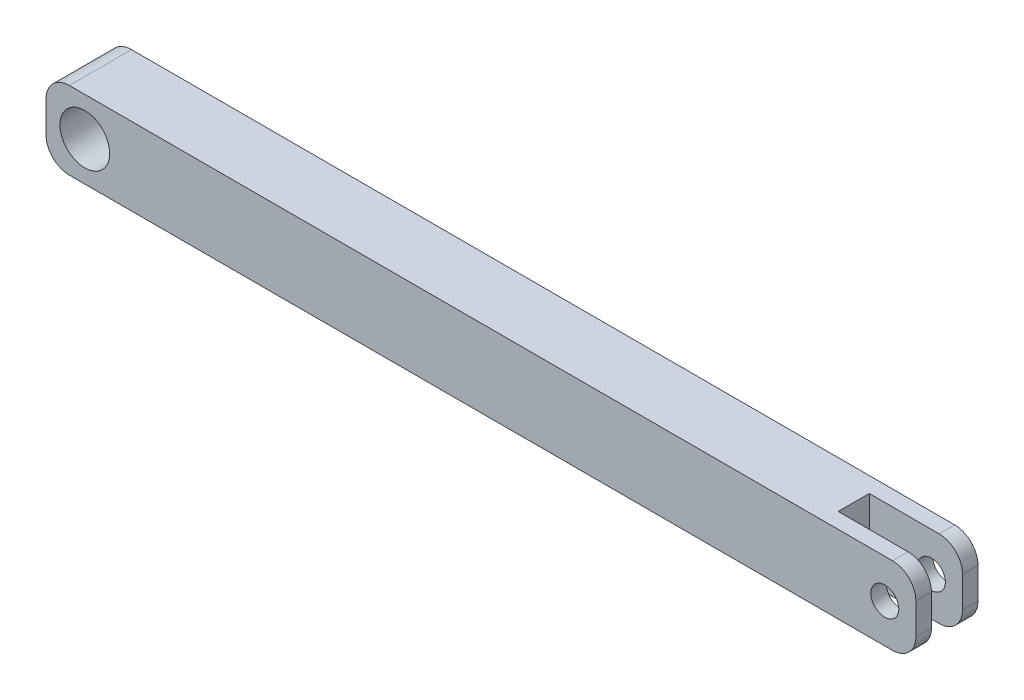
SolidWorks part; units mm, degrees
ref_plane "前视基准面" through (0, 0, 0) normal (0, 0, 1) x (1, 0, 0)
ref_plane "上视基准面" through (0, 0, 0) normal (0, 1, 0) x (1, 0, 0)
ref_plane "右视基准面" through (0, 0, 0) normal (1, 0, 0) x (0, 0, -1)
other "Configuration Table"
sketch "草图5" plane through (0, 0, 0) normal (0, 1, 0) x (1, 0, 0)
  line L0 (0, 0) -> (0, -3)
  line L4 (56, -3) -> (56, 0)
  line L8 (56, 0) -> (0, 0)
  line L9 (0, -3) -> (56, -3)
  dimension "D6" = 3
  dimension "D1" = 56
  dimension "D5" = 3
extrude "凸台-拉伸1" add sketch "草图5" along normal blind 5
sketch "草图6" plane through (0, 0, 3) normal (0, 0, 1) x (1, 0, 0)
  line L2 (0, 5) -> (0, 0) construction
  line L3 (0, 5) -> (56, 5) construction
  circle A0 centre (2.5, 2.5) radius 1.6
  dimension "D1" = 3.2
  dimension "D2" = 2.5
  dimension "D3" = 2.5
extrude "切除-拉伸1" cut sketch "草图6" against normal up to next
sketch "草图7" plane through (0, 0, 0) normal (0, 0, 1) x (1, 0, 0)
  line L0 (56, 5) -> (56, 0) construction
  circle A0 centre (54, 2.5) radius 0.9
  point P6 (56, 2.5)
  dimension "D1" = 1.8
  dimension "D2" = 2
extrude "切除-拉伸2" cut sketch "草图7" along normal up to next
fillet "圆角1" radius 1.5 4 edges at (56, 5, 1.5) (56, 0, 1.5) (0, 0, 1.5) (0, 5, 1.5)
sketch "草图8" plane through (0, 5, 0) normal (0, 1, 0) x (1, 0, 0)
  line L0 (56, 0) -> (56, -3) construction
  line L1 (56, -0.7) -> (50, -0.7)
  line L2 (56, -0.7) -> (56, -2.3)
  line L3 (56, -2.3) -> (50, -2.3)
  line L4 (50, -0.7) -> (50, -2.3)
  point P6 (56, -1.5)
  dimension "D1" = 1.6
  dimension "D2" = 6
extrude "切除-拉伸3" cut sketch "草图8" against normal blind 10
sketch "草图10" plane through (0, 0, 3) normal (0, 0, 1) x (1, 0, 0)
  line L4 (56, 1.5) -> (56, 3.5)
  line L5 (54.5, 5) -> (1.5, 5)
  line L6 (0, 3.5) -> (0, 1.5)
  line L7 (1.5, 0) -> (54.5, 0)
  line L8 (56, 1.5) -> (56, 3.5)
  line L9 (54.5, 5) -> (1.5, 5)
  line L10 (0, 3.5) -> (0, 1.5)
  line L11 (1.5, 0) -> (54.5, 0)
  circle A0 centre (2.5, 2.5) radius 1.6 construction
  circle A1 centre (2.5, 2.5) radius 1.6
  circle A2 centre (54, 2.5) radius 0.9 construction
  circle A3 centre (54, 2.5) radius 0.9
  arc A4 (56, 3.5) -> (54.5, 5) centre (54.5, 3.5) ccw
  arc A5 (1.5, 5) -> (0, 3.5) centre (1.5, 3.5) ccw
  arc A6 (0, 1.5) -> (1.5, 0) centre (1.5, 1.5) ccw
  arc A7 (54.5, 0) -> (56, 1.5) centre (54.5, 1.5) ccw
  arc A8 (56, 3.5) -> (54.5, 5) centre (54.5, 3.5) ccw
  arc A9 (1.5, 5) -> (0, 3.5) centre (1.5, 3.5) ccw
  arc A10 (0, 1.5) -> (1.5, 0) centre (1.5, 1.5) ccw
  arc A11 (54.5, 0) -> (56, 1.5) centre (54.5, 1.5) ccw
  dimension "D1" = 0
extrude "凸台-拉伸2" add sketch "草图10" along normal blind 0.5
sketch "草图11" plane through (0, 0, 0) normal (0, 0, -1) x (-1, 0, 0)
  line L4 (-1.5, 5) -> (-54.5, 5)
  line L5 (-56, 3.5) -> (-56, 1.5)
  line L6 (-54.5, 0) -> (-1.5, 0)
  line L7 (0, 1.5) -> (0, 3.5)
  line L8 (-1.5, 5) -> (-54.5, 5)
  line L9 (-56, 3.5) -> (-56, 1.5)
  line L10 (-54.5, 0) -> (-1.5, 0)
  line L11 (0, 1.5) -> (0, 3.5)
  circle A0 centre (-54, 2.5) radius 0.9 construction
  circle A1 centre (-2.5, 2.5) radius 1.6 construction
  circle A2 centre (-54, 2.5) radius 0.9
  circle A3 centre (-2.5, 2.5) radius 1.6
  arc A4 (-54.5, 5) -> (-56, 3.5) centre (-54.5, 3.5) ccw
  arc A5 (-56, 1.5) -> (-54.5, 0) centre (-54.5, 1.5) ccw
  arc A6 (-1.5, 0) -> (0, 1.5) centre (-1.5, 1.5) ccw
  arc A7 (0, 3.5) -> (-1.5, 5) centre (-1.5, 3.5) ccw
  arc A8 (-54.5, 5) -> (-56, 3.5) centre (-54.5, 3.5) ccw
  arc A9 (-56, 1.5) -> (-54.5, 0) centre (-54.5, 1.5) ccw
  arc A10 (-1.5, 0) -> (0, 1.5) centre (-1.5, 1.5) ccw
  arc A11 (0, 3.5) -> (-1.5, 5) centre (-1.5, 3.5) ccw
  dimension "D1" = 0
extrude "凸台-拉伸3" add sketch "草图11" along normal blind 0.5
sketch "草图12" plane through (0, 5, 0) normal (0, 1, 0) x (1, 0, 0)
  line L0 (50, -0.7) -> (50, -2.3) construction
  line L1 (56.2064, -2.5) -> (50, -2.5)
  line L2 (56.2064, -2.5) -> (56.2064, -0.5)
  line L3 (56.2064, -0.5) -> (50, -0.5)
  line L4 (50, -2.5) -> (50, -0.5)
  line L5 (56.2064, -2.5) -> (50, -0.5) construction
  line L6 (56.2064, -0.5) -> (50, -2.5) construction
  line L7 (54.5, -0.7) -> (50, -0.7) construction
  line L8 (50, -2.3) -> (54.5, -2.3) construction
  point P0 (53.1032, -1.5)
  point P5 (53.3117, -1.5141)
  dimension "D1" = 0.2
  dimension "D2" = 0.2
extrude "切除-拉伸4" cut sketch "草图12" against normal blind 10
